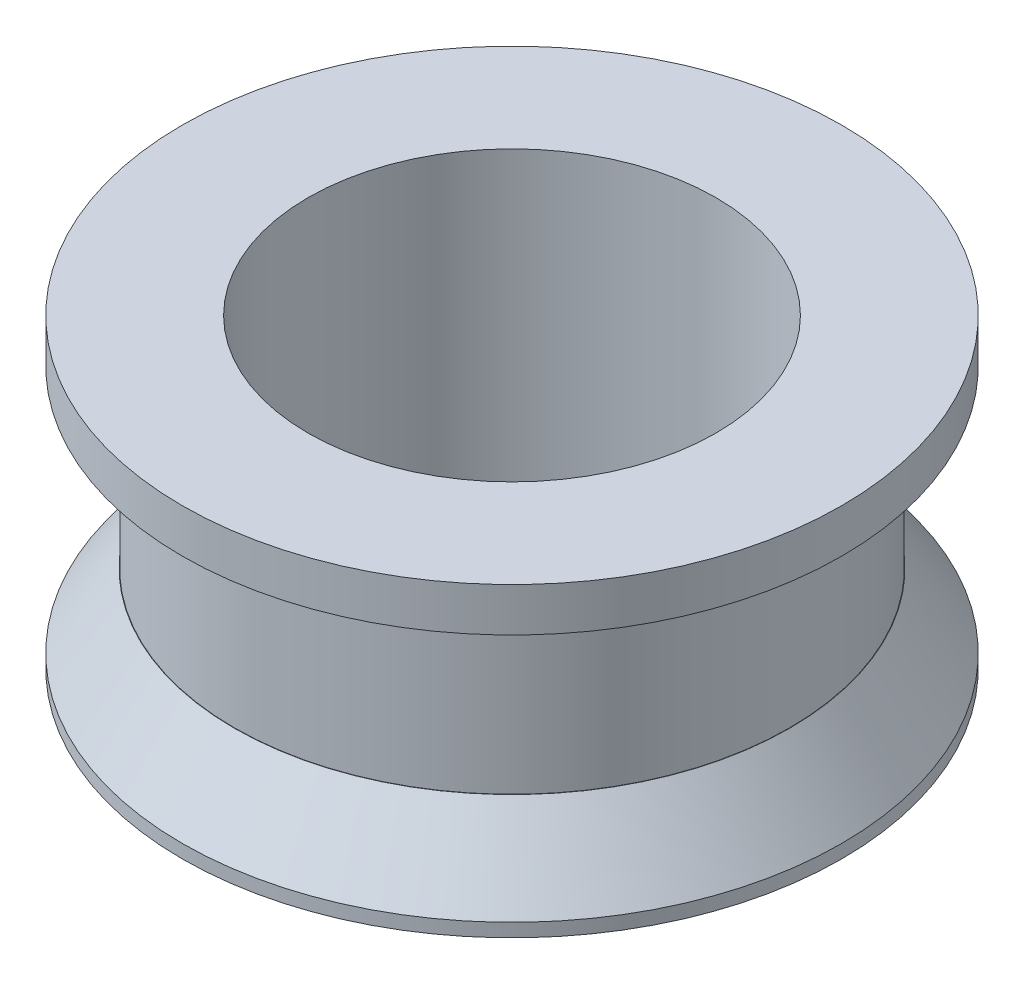
SolidWorks part; units mm, degrees
material "ABS"
ref_plane "Front Plane" through (0, 0, 0) normal (0, 0, 1) x (1, 0, 0)
ref_plane "Top Plane" through (0, 0, 0) normal (0, 1, 0) x (1, 0, 0)
ref_plane "Right Plane" through (0, 0, 0) normal (1, 0, 0) x (0, 0, -1)
sketch "Sketch1" plane through (0, 0, 0) normal (0, 1, 0) x (1, 0, 0)
  circle A0 centre (0, 0) radius 9.525
  circle A1 centre (0, 0) radius 7
  dimension "D1" = 19.05
  dimension "D2" = 14
extrude "Boss-Extrude1" add sketch "Sketch1" along normal blind 6
sketch "Sketch2" plane through (0, 6, 0) normal (0, 1, 0) x (1, 0, 0)
  circle A0 centre (0, 0) radius 11.3158
  circle A1 centre (0, 0) radius 7
extrude "Boss-Extrude2" add sketch "Sketch2" along normal blind 1.5
sketch "Sketch3" plane through (0, 0, 0) normal (0, -1, 0) x (1, 0, 0)
  circle A0 centre (0, 0) radius 11.3158
  circle A1 centre (0, 0) radius 7
extrude "Boss-Extrude4" add sketch "Sketch3" along normal blind 3
chamfer "Chamfer4" distance 1.778 angle 55 1 edges at (0, 0, -11.3158)
